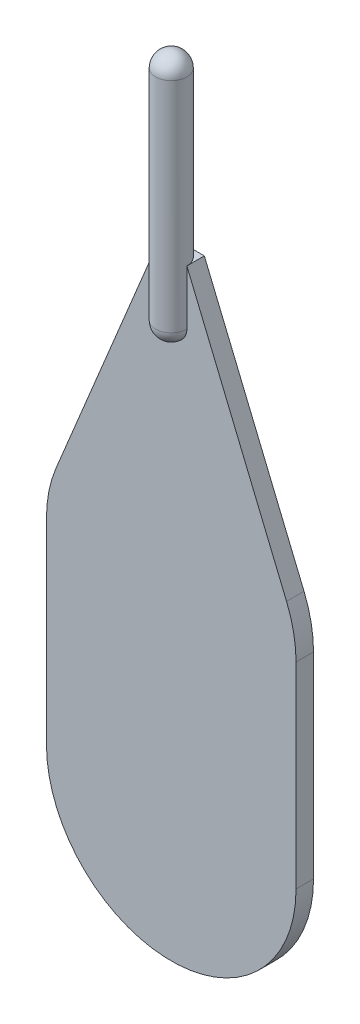
SolidWorks part; units mm, degrees
ref_plane "Front Plane" through (0, 0, 0) normal (0, 0, 1) x (1, 0, 0)
ref_plane "Top Plane" through (0, 0, 0) normal (0, 1, 0) x (1, 0, 0)
ref_plane "Right Plane" through (0, 0, 0) normal (1, 0, 0) x (0, 0, -1)
sketch "Sketch1" plane through (0, 0, 0) normal (0, 0, 1) x (1, 0, 0)
  line L5 (28.3897, 3.0759) -> (28.3897, 13.0759)
  line L6 (15.6897, 3.0759) -> (15.6897, 13.0759)
  line L7 (21.2459, 27.753) -> (16.173, 15.5059)
  line L8 (22.8334, 27.753) -> (27.9063, 15.5059)
  line L9 (22.8334, 27.753) -> (21.2459, 27.753)
  arc A3 (15.6897, 3.0759) -> (28.3897, 3.0759) centre (22.0397, 3.0759) ccw
  arc A4 (28.3897, 13.0759) -> (27.9063, 15.5059) centre (22.0397, 13.0759) ccw
  arc A5 (16.173, 15.5059) -> (15.6897, 13.0759) centre (22.0397, 13.0759) ccw
extrude "Boss-Extrude1" add sketch "Sketch1" along normal blind 0.889
sketch "Sketch2" plane through (0, 0, 0.889) normal (0, 0, 1) x (1, 0, 0)
  line L4 (22.8334, 27.753) -> (21.2459, 27.753) construction
  line L5 (22.0397, 24.1738) -> (22.0397, 36.8738)
  line L6 (21.2459, 36.08) -> (21.2459, 24.9675)
  arc A2 (22.0397, 24.1738) -> (21.2459, 24.9675) centre (22.0397, 24.9675) cw
  arc A3 (21.2459, 36.08) -> (22.0397, 36.8738) centre (22.0397, 36.08) cw
revolve "Revolve1" add sketch "Sketch2" angle 360 about L5
